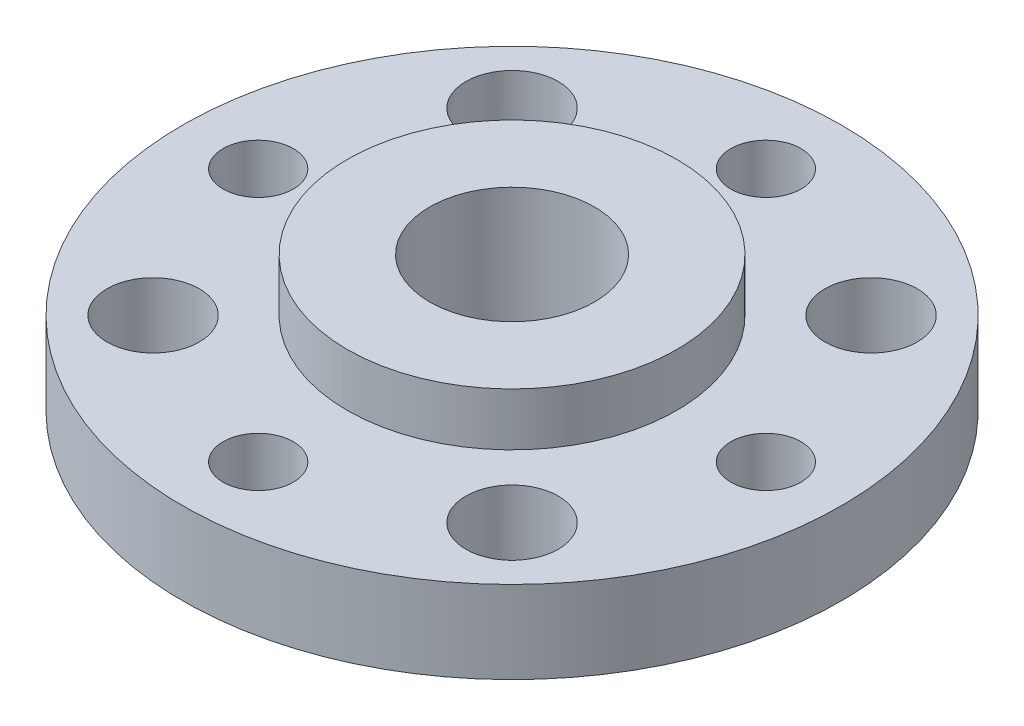
SolidWorks part; units mm, degrees
ref_plane "Front Plane" through (0, 0, 0) normal (0, 0, 1) x (1, 0, 0)
ref_plane "Top Plane" through (0, 0, 0) normal (0, 1, 0) x (1, 0, 0)
ref_plane "Right Plane" through (0, 0, 0) normal (1, 0, 0) x (0, 0, -1)
sketch "Sketch1" plane through (0, 0, 0) normal (0, 0, 1) x (1, 0, 0)
  line L0 (12.6962, 3.175) -> (0, 3.175)
  line L1 (0, 3.175) -> (0, 0)
  line L2 (0, 0) -> (12.6962, 0)
  line L3 (12.6962, 0) -> (12.6962, 3.175)
  line L4 (0, 3.175) -> (0, 0) construction
revolve "Revolve1" add sketch "Sketch1" angle 360 about L4
sketch "Sketch2" plane through (0, 3.175, 0) normal (0, 1, 0) x (-1, 0, 0)
  circle A0 centre (0, 0) radius 6.3462
extrude "Boss-Extrude1" add sketch "Sketch2" along normal blind 2.032
hole_wizard "M2.5 Clearance Hole1" positions "Sketch4" profile "Sketch3" hole size "M2.5" standard "ANSI Metric"
sketch "Sketch4" plane through (0, 3.175, 0) normal (0, 1, 0) x (1, 0, 0)
  point P0 (-9.779, 0)
  point P1 (0, 9.779)
  point P2 (9.779, 0)
  point P3 (0, -9.779)
sketch "Sketch3" plane through (-9.779, 3.175, 0) normal (1, 0, 0) x (0, 0, 1)
  line L0 (0, 0) -> (0, 3.175)
  line L1 (0, 3.175) -> (1.3525, 3.175)
  line L2 (1.3525, 3.175) -> (1.3525, 0)
  line L5 (1.3525, 0) -> (0, 0)
  line L11 (0, -6.35) -> (0, 107.95) construction
  dimension "Thru Hole Dia." = 2.7051
  dimension "Thru Hole Depth" = 3.175
hole_wizard "M3 Clearance Hole1" positions "Sketch8" profile "Sketch7" hole size "M3" standard "ANSI Metric"
sketch "Sketch8" plane through (0, 0, 0) normal (0, -1, 0) x (-1, 0, 0)
  point P0 (6.9148, 6.9148)
  point P1 (-6.9148, 6.9148)
  point P2 (-6.9148, -6.9148)
  point P3 (6.9148, -6.9148)
sketch "Sketch7" plane through (-6.9148, 0, -6.9148) normal (1, 0, 0) x (0, 0, -1)
  line L0 (0, 0) -> (0, 5.207)
  line L1 (0, 5.207) -> (1.778, 5.207)
  line L2 (1.778, 5.207) -> (1.778, 0)
  line L5 (1.778, 0) -> (0, 0)
  line L11 (0, -6.35) -> (0, 107.95) construction
  dimension "Thru Hole Dia." = 3.556
  dimension "Thru Hole Depth" = 5.207
sketch "Sketch9" plane through (0, 5.207, 0) normal (0, 1, 0) x (1, 0, 0)
  circle A0 centre (0, 0) radius 3.175
extrude "Cut-Extrude1" cut sketch "Sketch9" against normal through all
